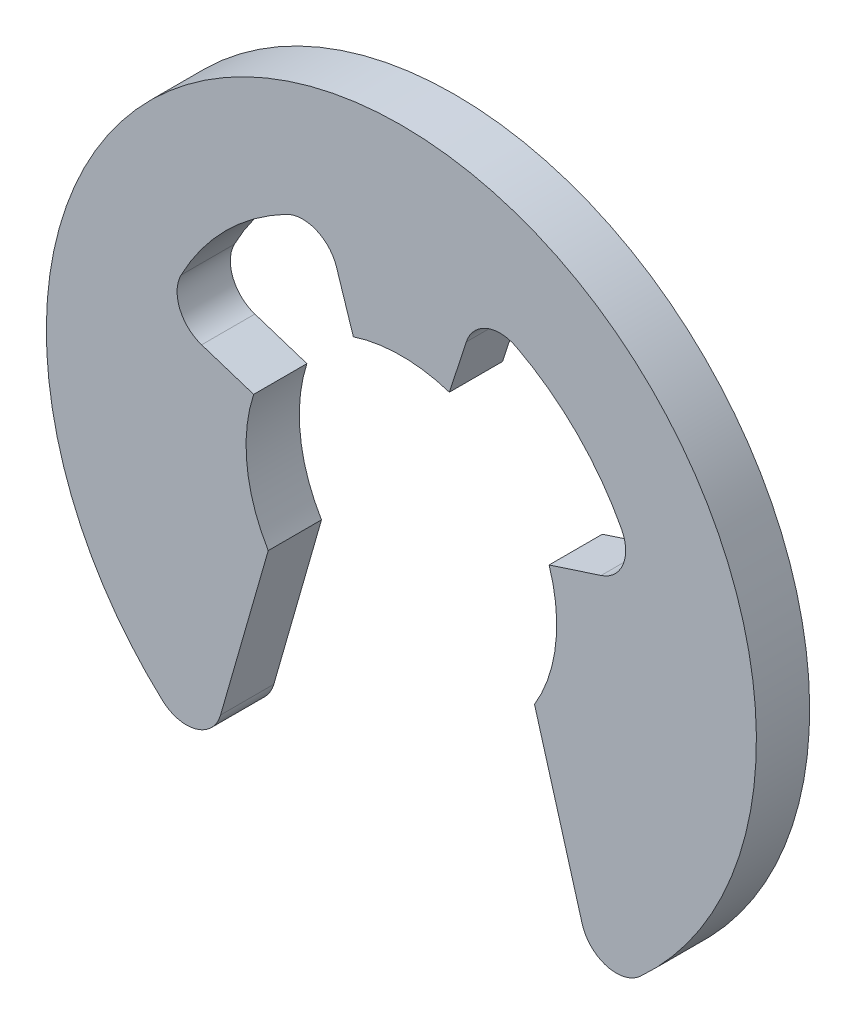
SolidWorks part; units mm, degrees
ref_plane "Front" through (0, 0, 0) normal (0, 0, 1) x (1, 0, 0)
ref_plane "Top" through (0, 0, 0) normal (0, 1, 0) x (1, 0, 0)
ref_plane "Right" through (0, 0, 0) normal (1, 0, 0) x (0, 0, -1)
sketch "Sketch1" plane through (0, 0, 0) normal (0, 0, 1) x (1, 0, 0)
  line L0 (0, 2.1875) -> (0, -1.9262) construction
  line L1 (-1.6904, 0) -> (1.9829, 0) construction
  line L2 (0, 0) -> (1.2361, 3.8042) construction
  line L3 (0, 0) -> (3.8042, 1.2361) construction
  line L4 (0.7313, 2.2506) -> (0.5408, 1.6643)
  line L5 (1.6643, 0.5408) -> (2.2506, 0.7313)
  line L6 (1.5, -0.9014) -> (2.037, -2.7741)
  line L7 (-1.6643, 0.5408) -> (-2.2506, 0.7313)
  line L8 (-0.7313, 2.2506) -> (-0.5408, 1.6643)
  line L9 (-1.5, -0.9014) -> (-2.037, -2.7741)
  arc A0 (2.6906, -2.9599) -> (-2.6906, -2.9599) centre (0, 0) ccw
  arc A1 (1.5, -0.9014) -> (1.6643, 0.5408) centre (0, 0) ccw
  arc A2 (2.4815, 1.297) -> (1.297, 2.4815) centre (0, 0) ccw
  arc A3 (2.4815, 1.297) -> (2.2506, 0.7313) centre (2.127, 1.1117) cw
  arc A4 (2.037, -2.7741) -> (2.6906, -2.9599) centre (2.4215, -2.6639) ccw
  arc A5 (-2.037, -2.7741) -> (-2.6906, -2.9599) centre (-2.4215, -2.6639) cw
  arc A6 (0.5408, 1.6643) -> (-0.5408, 1.6643) centre (0, 0) ccw
  arc A7 (0.7313, 2.2506) -> (1.297, 2.4815) centre (1.1117, 2.127) cw
  arc A8 (-1.5, -0.9014) -> (-1.6643, 0.5408) centre (0, 0) cw
  arc A9 (-2.4815, 1.297) -> (-2.2506, 0.7313) centre (-2.127, 1.1117) ccw
  arc A10 (-0.7313, 2.2506) -> (-1.297, 2.4815) centre (-1.1117, 2.127) ccw
  arc A11 (-2.4815, 1.297) -> (-1.297, 2.4815) centre (0, 0) cw
  point P17 (2.663, 0.8652)
  point P25 (0.8652, 2.663)
  dimension "D0" = 8
  dimension "d" = 3.5
  dimension "r2" = 0.4
  dimension "r1" = 0.4
  dimension "R" = 2.8
  dimension "D2" = 18
  dimension "D3" = 18
  dimension "D4" = 16
  dimension "B" = 3
extrude "Body" add sketch "Sketch1" against normal blind 0.6
equation "\"r2@Sketch1\" = \"r1@Sketch1\""
